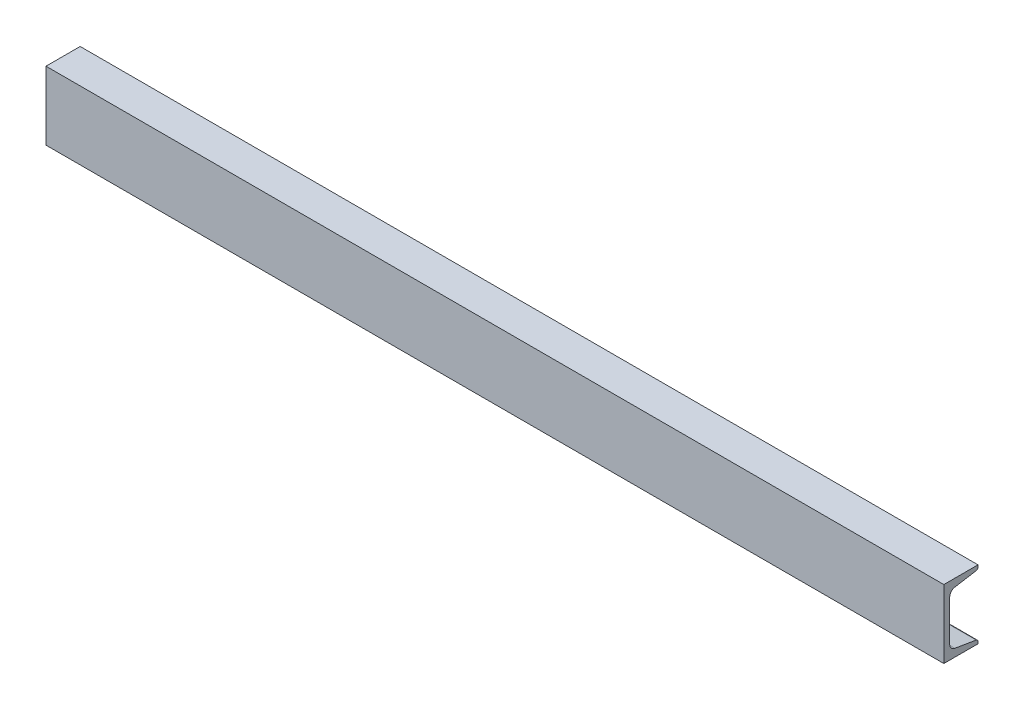
SolidWorks part; units mm, degrees
ref_plane "Alzado" through (0, 0, 0) normal (0, 0, 1) x (1, 0, 0)
ref_plane "Planta" through (0, 0, 0) normal (0, 1, 0) x (1, 0, 0)
ref_plane "Vista lateral" through (0, 0, 0) normal (1, 0, 0) x (0, 0, -1)
sketch "Croquis1" plane through (0, 0, 0) normal (0, 1, 0) x (1, 0, 0)
  line L0 (0, 0) -> (1000, 0)
  dimension "D1" = 1000
other "Canal c 3 X 5(1)"
ref_plane "Plano1" through (0, 0, 0) normal (1, 0, 0) x (0, 0, -1)
sketch "Sketch12" plane through (0, 0, 0) normal (1, 0, 0) x (0, 0, -1)
  line L0 (0, -38.1) -> (0, 38.1)
  line L1 (0, 38.1) -> (38.0492, 38.1)
  line L2 (0, -38.1) -> (38.0492, -38.1)
  line L5 (31.75, -31.1658) -> (6.35, -31.1658) construction
  line L6 (0, 0) -> (6.5532, 0) construction
  line L12 (6.5532, 22.7314) -> (6.5532, -22.7314)
  line L15 (38.0492, 38.1) -> (38.0492, 35.9423)
  line L16 (38.0492, -38.1) -> (38.0492, -35.9423)
  line L17 (12.2837, 29.4961) -> (35.9268, 33.4369)
  line L18 (12.2837, -29.4961) -> (35.9268, -33.4369)
  arc A9 (6.5532, -22.7314) -> (12.2837, -29.4961) centre (13.4112, -22.7314) ccw
  arc A10 (6.5532, 22.7314) -> (12.2837, 29.4961) centre (13.4112, 22.7314) cw
  arc A11 (38.0492, 35.9423) -> (35.9268, 33.4369) centre (35.5092, 35.9423) cw
  arc A12 (38.0492, -35.9423) -> (35.9268, -33.4369) centre (35.5092, -35.9423) ccw
  point P4 (38.0492, 33.7907)
  point P5 (38.0492, -33.7907)
  point P6 (3.2766, 0)
  point P7 (19.0246, 38.1)
  point P12 (19.0246, -38.1)
  point P13 (0, 0)
  dimension "RI" = 6.858
  dimension "D2" = 9.463
  dimension "RA" = 2.54
  dimension "Depth" = 76.2
  dimension "BF" = 38.0492
  dimension "TW" = 6.5532
  dimension "flange" = 2.1577
  dimension "TF" = 6.9342
